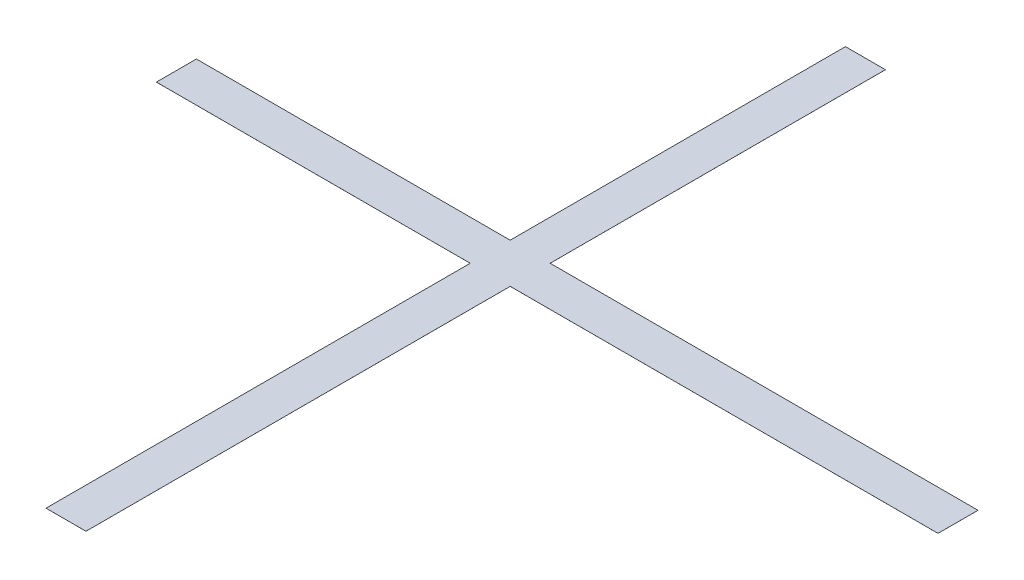
SolidWorks part; units mm, degrees
ref_plane "Plano frontal" through (0, 0, 0) normal (0, 0, 1) x (1, 0, 0)
ref_plane "Plano superior" through (0, 0, 0) normal (0, 1, 0) x (1, 0, 0)
ref_plane "Plano direito" through (0, 0, 0) normal (1, 0, 0) x (0, 0, -1)
sketch "Esboço1" plane through (0, 0, 0) normal (0, 1, 0) x (1, 0, 0)
  line L0 (-1093, 595.536) -> (-1073, 595.536)
  line L1 (0, 0) -> (18.9344, 0)
  line L2 (0, 0) -> (0, 766.8662)
  line L3 (0, 766.8662) -> (18.9344, 766.8662)
  line L4 (18.9344, 0) -> (18.9344, 766.8662)
  line L5 (-381.6968, 766.8662) -> (-362.7624, 766.8662)
  line L6 (-381.6968, 766.8662) -> (-381.6968, 345.536)
  line L7 (-381.6968, 345.536) -> (-362.7624, 345.536)
  line L8 (-362.7624, 766.8662) -> (-362.7624, 345.536)
  line L9 (-858.9344, 645.536) -> (-840, 645.536)
  line L10 (-858.9344, 645.536) -> (-858.9344, 345.536)
  line L11 (-858.9344, 345.536) -> (-840, 345.536)
  line L12 (-840, 645.536) -> (-840, 345.536)
  line L13 (-853.5858, 925.2213) -> (-1253.5858, 925.2213)
  line L14 (-853.5858, 925.2213) -> (-853.5858, 945.2213)
  line L15 (-853.5858, 945.2213) -> (-1253.5858, 945.2213)
  line L16 (-1253.5858, 925.2213) -> (-1253.5858, 945.2213)
  line L17 (-1093, 595.536) -> (-1093, 195.536)
  line L18 (-1093, 195.536) -> (-1073, 195.536)
  line L19 (-1073, 595.536) -> (-1073, 195.536)
  line L21 (-858.9344, 427.7897) -> (-1250.0103, 427.7897)
  line L23 (-858.9344, 407.7897) -> (-1250.0103, 407.7897)
  line L24 (-1250.0103, 427.7897) -> (-1250.0103, 407.7897)
  line L33 (-1439.6613, 239.7512) -> (-1560.0448, 239.7512)
  line L34 (-1439.6613, 239.7512) -> (-1439.6613, 219.7512)
  line L35 (-1439.6613, 219.7512) -> (-1560.0448, 219.7512)
  line L36 (-1560.0448, 239.7512) -> (-1560.0448, 219.7512)
  line L37 (-1627.2015, 576.144) -> (-1607.2015, 576.144)
  line L38 (-1627.2015, 576.144) -> (-1627.2015, 317.0654)
  line L39 (-1627.2015, 317.0654) -> (-1607.2015, 317.0654)
  line L40 (-1607.2015, 576.144) -> (-1607.2015, 317.0654)
  line L41 (-1627.2015, 769.6927) -> (-1607.2015, 769.6927)
  line L42 (-1627.2015, 769.6927) -> (-1627.2015, 1019.6927)
  line L43 (-1627.2015, 1019.6927) -> (-1607.2015, 1019.6927)
  line L44 (-1607.2015, 769.6927) -> (-1607.2015, 1019.6927)
  line L45 (404.0502, 922.489) -> (424.0502, 922.489)
  line L47 (404.0502, 522.489) -> (424.0502, 522.489)
  line L51 (247.0399, 754.7427) -> (247.0399, 734.7427)
  line L52 (638.1158, 754.7427) -> (638.1158, 734.7427)
  line L56 (424.0502, 922.489) -> (424.0502, 754.7427)
  line L58 (424.0502, 522.489) -> (424.0502, 734.7427)
  line L60 (404.0502, 922.489) -> (404.0502, 754.7427)
  line L62 (404.0502, 522.489) -> (404.0502, 734.7427)
  line L64 (247.0399, 754.7427) -> (404.0502, 754.7427)
  line L65 (424.0502, 754.7427) -> (638.1158, 754.7427)
  line L66 (247.0399, 734.7427) -> (404.0502, 734.7427)
  line L67 (424.0502, 734.7427) -> (638.1158, 734.7427)
  arc A6 (-381.6968, 766.8662) -> (18.9344, 766.8662) centre (-181.3812, 766.8662) cw
  arc A7 (-362.7624, 766.8662) -> (0, 766.8662) centre (-181.3812, 766.8662) cw
  arc A8 (-362.7624, 345.536) -> (-858.9344, 345.536) centre (-610.8484, 345.536) cw
  arc A9 (-381.6968, 345.536) -> (-840, 345.536) centre (-610.8484, 345.536) cw
  arc A10 (-840, 645.536) -> (-803.6955, 702.0415) centre (-777.8744, 645.536) cw
  arc A11 (-803.6955, 702.0415) -> (-853.5858, 945.2213) centre (-856.6336, 817.8884) ccw
  arc A12 (-858.9344, 645.536) -> (-814.4955, 717.9247) centre (-777.7563, 645.536) cw
  arc A13 (-814.4955, 717.9247) -> (-853.5858, 925.2213) centre (-864.2122, 815.8835) ccw
  arc A14 (-1093, 595.536) -> (-1188.5366, 677.9223) centre (-1176.2913, 595.536) ccw
  arc A15 (-1188.5366, 677.9223) -> (-1354.3411, 742.8189) centre (-1214.8489, 854.9525) cw
  arc A16 (-1354.3411, 742.8189) -> (-1253.5858, 945.2213) centre (-1257.3278, 820.805) cw
  arc A17 (-1073, 595.536) -> (-1188.5366, 698.0004) centre (-1176.2038, 595.536) ccw
  arc A18 (-1188.5366, 698.0004) -> (-1341.8208, 766.8662) centre (-1207.9995, 859.705) cw
  arc A19 (-1341.8208, 766.8662) -> (-1253.5858, 925.2213) centre (-1258.876, 824.4093) cw
  arc A22 (-1368.7558, 309.7722) -> (-1439.6613, 219.7512) centre (-1474.849, 320.402) cw
  arc A23 (-1388.5562, 309.7722) -> (-1439.6613, 239.7512) centre (-1477.6183, 321.1143) cw
  arc A24 (-1388.5562, 309.7722) -> (-1250.0103, 427.7897) centre (-1254.4723, 292.6965) cw
  arc A25 (-1607.2015, 317.0654) -> (-1560.0448, 239.7512) centre (-1520.2441, 317.0654) ccw
  arc A26 (-1627.2015, 317.0654) -> (-1560.0448, 219.7512) centre (-1523.1159, 317.0654) ccw
  arc A27 (-1368.7558, 309.7722) -> (-1250.0103, 407.7897) centre (-1259.9289, 298.8686) cw
extrude "Ressalto-extrusão19" add sketch "Esboço1" along normal blind 0.01 contours L65 L52 L67 L58 L47 L62 L66 L51 L64 L60 L45 L56
